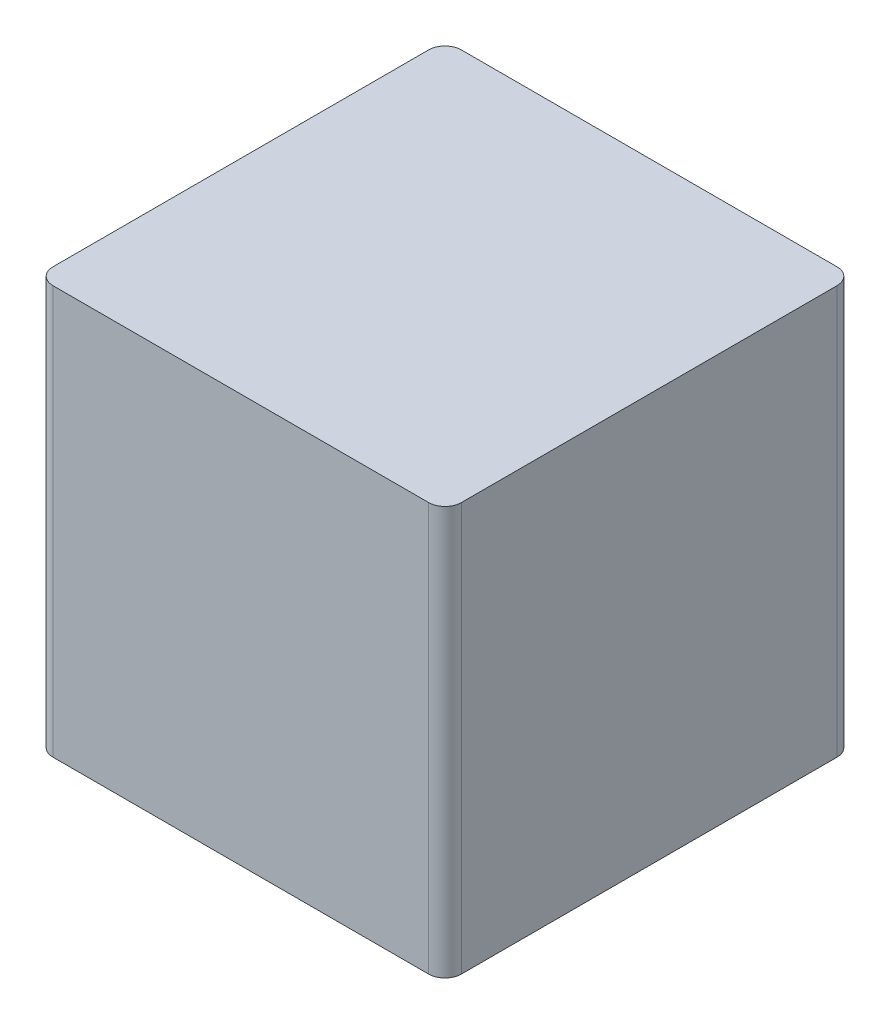
SolidWorks part; units mm, degrees
ref_plane "Front Plane" through (0, 0, 0) normal (0, 0, 1) x (1, 0, 0)
ref_plane "Top Plane" through (0, 0, 0) normal (0, 1, 0) x (1, 0, 0)
ref_plane "Right Plane" through (0, 0, 0) normal (1, 0, 0) x (0, 0, -1)
sketch "Sketch1" plane through (0, 0, 0) normal (0, 1, 0) x (1, 0, 0)
  line L1 (31.75, 31.75) -> (-31.75, 31.75)
  line L2 (31.75, 31.75) -> (31.75, -31.75)
  line L3 (31.75, -31.75) -> (-31.75, -31.75)
  line L4 (-31.75, 31.75) -> (-31.75, -31.75)
  line L5 (31.75, 31.75) -> (-31.75, -31.75) construction
  line L6 (31.75, -31.75) -> (-31.75, 31.75) construction
  point P0 (0, 0)
  dimension "D1" = 63.5
  dimension "D2" = 63.5
extrude "Boss-Extrude1" add sketch "Sketch1" along normal blind 63.5 contours L2 L1 L4 L3
fillet "Fillet1" radius 2.54 4 edges at (-31.75, 31.75, 31.75) (-31.75, 31.75, -31.75) (31.75, 31.75, -31.75) (31.75, 31.75, 31.75)
